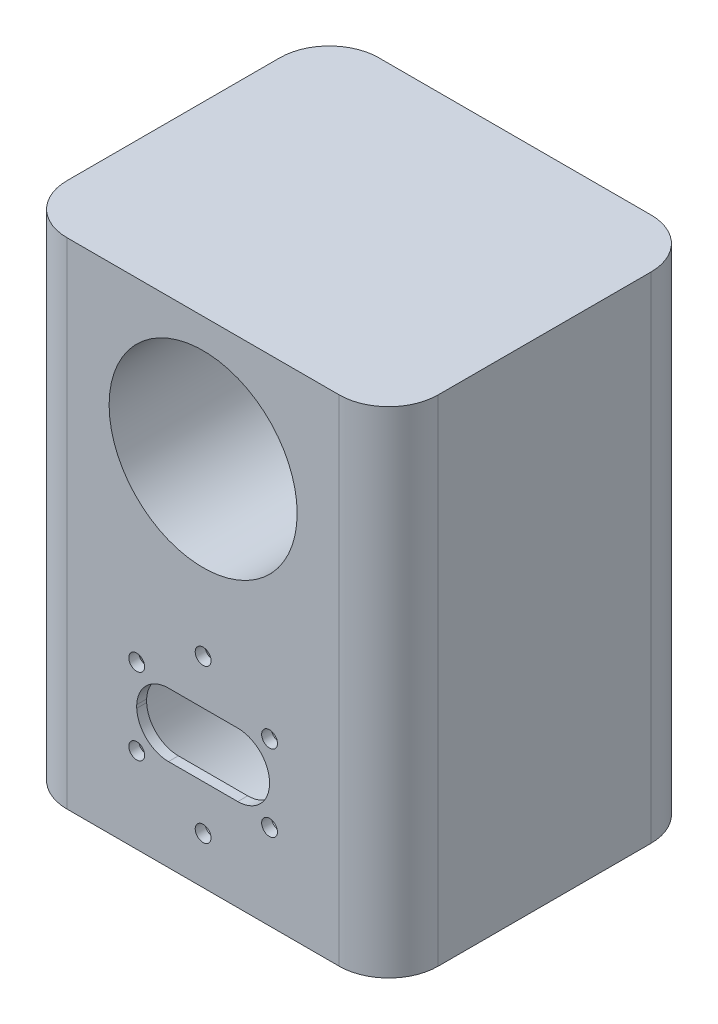
SolidWorks part; units mm, degrees
ref_plane "前视基准面" through (0, 0, 0) normal (0, 0, 1) x (1, 0, 0)
ref_plane "上视基准面" through (0, 0, 0) normal (0, 1, 0) x (1, 0, 0)
ref_plane "右视基准面" through (0, 0, 0) normal (1, 0, 0) x (0, 0, -1)
other "Configuration Table"
sketch "草图1" plane through (0, 0, 0) normal (0, 1, 0) x (1, 0, 0)
  line L1 (-27.5, 31.5) -> (27.5, 31.5)
  line L2 (-37.5, 21.5) -> (-37.5, -21.5)
  line L3 (-27.5, -31.5) -> (27.5, -31.5)
  line L4 (37.5, 21.5) -> (37.5, -21.5)
  line L5 (0, -31.5) -> (0, 31.5) construction
  line L6 (-37.5, 0) -> (37.5, 0) construction
  arc A0 (-37.5, -21.5) -> (-27.5, -31.5) centre (-27.5, -21.5) ccw
  arc A1 (27.5, -31.5) -> (37.5, -21.5) centre (27.5, -21.5) ccw
  arc A2 (27.5, 31.5) -> (37.5, 21.5) centre (27.5, 21.5) cw
  arc A3 (-27.5, 31.5) -> (-37.5, 21.5) centre (-27.5, 21.5) ccw
  point P0 (0, 0)
  point P8 (37.5, -31.5)
  point P11 (37.5, 31.5)
  point P15 (-37.5, 31.5)
  dimension "D3" = 10
  dimension "D1" = 63
  dimension "D2" = 75
extrude "凸台-拉伸1" add sketch "草图1" against normal blind 100
ref_plane "基准面1" through (0, 0, 31.5) normal (0, 0, 1) x (1, 0, 0)
sketch "草图3" plane through (0, 0, 31.5) normal (0, 0, 1) x (1, 0, 0)
  line L0 (0, 0) -> (0, -100) construction
  line L1 (0.0046, -41.0948) -> (13.428, -33.3448)
  line L2 (-27.5, -100) -> (27.5, -100) construction
  line L3 (13.428, -33.3448) -> (13.428, -17.8448)
  line L8 (0, -35) -> (0, -15) construction
  line L9 (-20.5, -25) -> (20.5, -25) construction
  line L10 (13.428, -17.8448) -> (0.0046, -10.0948)
  line L11 (0.0046, -10.0948) -> (-13.4188, -17.8448)
  line L12 (-13.4188, -17.8448) -> (-13.4188, -33.3448)
  line L13 (-13.4188, -33.3448) -> (0.0046, -41.0948)
  line L14 (7.0046, -25.5948) -> (-6.9954, -25.5948) construction
  line L15 (7.0046, -32.0224) -> (-6.9954, -32.0224)
  line L16 (7.0046, -19.1672) -> (-6.9954, -19.1672)
  circle A4 centre (0.0046, -25.5948) radius 13.4234
  circle A5 centre (13.428, -33.3448) radius 1.6
  circle A6 centre (0.0046, -41.0948) radius 1.6
  circle A7 centre (-13.4188, -33.3448) radius 1.6
  circle A8 centre (-13.4188, -17.8448) radius 1.6
  circle A9 centre (13.428, -17.8448) radius 1.6
  circle A10 centre (0.0046, -10.0948) radius 1.6
  arc A11 (7.0046, -32.0224) -> (7.0046, -19.1672) centre (7.0046, -25.5948) ccw
  arc A12 (-6.9954, -19.1672) -> (-6.9954, -32.0224) centre (-6.9954, -25.5948) ccw
  circle A13 centre (0.0046, -25.5948) radius 19
  point P5 (0, -25)
  point P19 (0.0046, -25.5948)
ref_plane "基准面2" through (0, 0, -31.5) normal (0, 0, -1) x (-1, 0, 0)
sketch "草图4" plane through (0, 0, -31.5) normal (0, 0, -1) x (-1, 0, 0)
  line L0 (0, 0) -> (0, -100) construction
  line L1 (-27.5, -100) -> (27.5, -100) construction
  line L2 (0, -75) -> (7, -75)
  line L7 (0, -85) -> (0, -65) construction
  line L8 (-20.5, -75) -> (20.5, -75) construction
  line L9 (0, -90.5) -> (13.4234, -82.75)
  line L10 (13.4234, -82.75) -> (13.4234, -67.25)
  line L11 (13.4234, -67.25) -> (0, -59.5)
  line L12 (0, -59.5) -> (-13.4234, -67.25)
  line L13 (-13.4234, -67.25) -> (-13.4234, -82.75)
  line L14 (-13.4234, -82.75) -> (0, -90.5)
  line L16 (0, -75) -> (-7, -75)
  line L17 (7, -75) -> (-7, -75) construction
  line L18 (7, -81.4276) -> (-7, -81.4276)
  line L19 (7, -68.5724) -> (-7, -68.5724)
  circle A7 centre (0, -75) radius 13.4234
  circle A8 centre (0, -75) radius 13.4234 construction
  circle A9 centre (13.4234, -82.75) radius 1.6
  circle A10 centre (0, -90.5) radius 1.6
  circle A11 centre (-13.4234, -82.75) radius 1.6
  circle A12 centre (-13.4234, -67.25) radius 1.6
  circle A14 centre (13.4234, -67.25) radius 1.6
  circle A15 centre (0, -59.5) radius 1.6
  arc A16 (7, -81.4276) -> (7, -68.5724) centre (7, -75) ccw
  arc A17 (-7, -68.5724) -> (-7, -81.4276) centre (-7, -75) ccw
  circle A18 centre (0, -75) radius 19
  point P5 (0, -75)
  point P19 (0, -75)
  dimension "D1" = 26.8468
  dimension "D3" = 15.5
  dimension "D2" = 13.4234
sketch "草图5" plane through (0, 0, 31.5) normal (0, 0, 1) x (1, 0, 0)
  circle A0 centre (0, -25) radius 19
sketch "草图7" plane through (0, 0, -31.5) normal (0, 0, -1) x (-1, 0, 0)
  line L0 (-27.5, 0) -> (27.5, 0) construction
  circle A0 centre (0, -75) radius 19
extrude "切除-拉伸7" cut sketch "草图4" against normal through all
sketch "草图8" plane through (0, 0, 0) normal (0, 1, 0) x (1, 0, 0)
  line L2 (27.5, 31.5) -> (-27.5, 31.5)
  line L3 (27.5, 31.5) -> (27.5, -31.5)
  line L4 (27.5, -31.5) -> (-27.5, -31.5)
  line L5 (-27.5, 31.5) -> (-27.5, -31.5)
  arc A0 (-37.5, -21.5) -> (-27.5, -31.5) centre (-27.5, -21.5) ccw construction
  dimension "D1" = 63
extrude "切除-拉伸8" cut sketch "草图7" against normal blind 61
extrude "切除-拉伸9" cut sketch "草图3" against normal through all contours L16 A12 A4 L15 A11 | A5 | A6 | A7 | A8 | A10 | A9
extrude "切除-拉伸10" cut sketch "草图5" against normal blind 61
